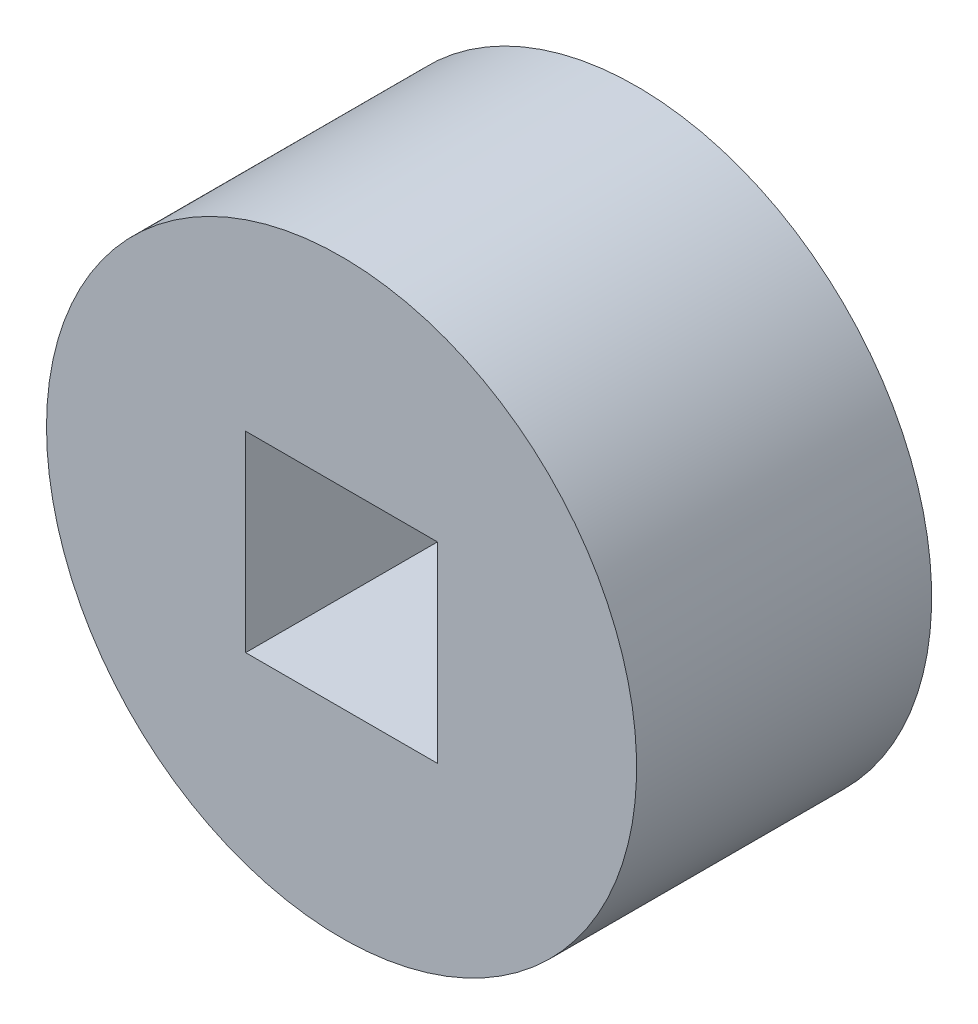
SolidWorks part; units mm, degrees
ref_plane "Plan de face" through (0, 0, 0) normal (0, 0, 1) x (1, 0, 0)
ref_plane "Plan de dessus" through (0, 0, 0) normal (0, 1, 0) x (1, 0, 0)
ref_plane "Plan de droite" through (0, 0, 0) normal (1, 0, 0) x (0, 0, -1)
sketch "Esquisse1" plane through (0, 0, 0) normal (0, 1, 0) x (1, 0, 0)
  line L0 (0, 0) -> (8, 0)
  line L1 (8, 0) -> (8, 8)
  line L2 (8, 8) -> (0, 8)
  line L3 (0, 8) -> (0, 0)
  dimension "D1" = 8
  dimension "D2" = 8
revolve "Révolution2" add sketch "Esquisse1" angle 360 about L3
sketch "Esquisse3" plane through (0, 0, 0) normal (0, 0, 1) x (1, 0, 0)
  line L0 (-2.6, -2.6) -> (2.6, -2.6)
  line L1 (2.6, -2.6) -> (2.6, 2.6)
  line L2 (-2.6, 2.6) -> (2.6, 2.6)
  line L3 (-2.6, -2.6) -> (-2.6, 2.6)
  dimension "D1" = 5.2
extrude "Enlèv. mat.-Extru.1" cut sketch "Esquisse3" against normal blind 5.5
